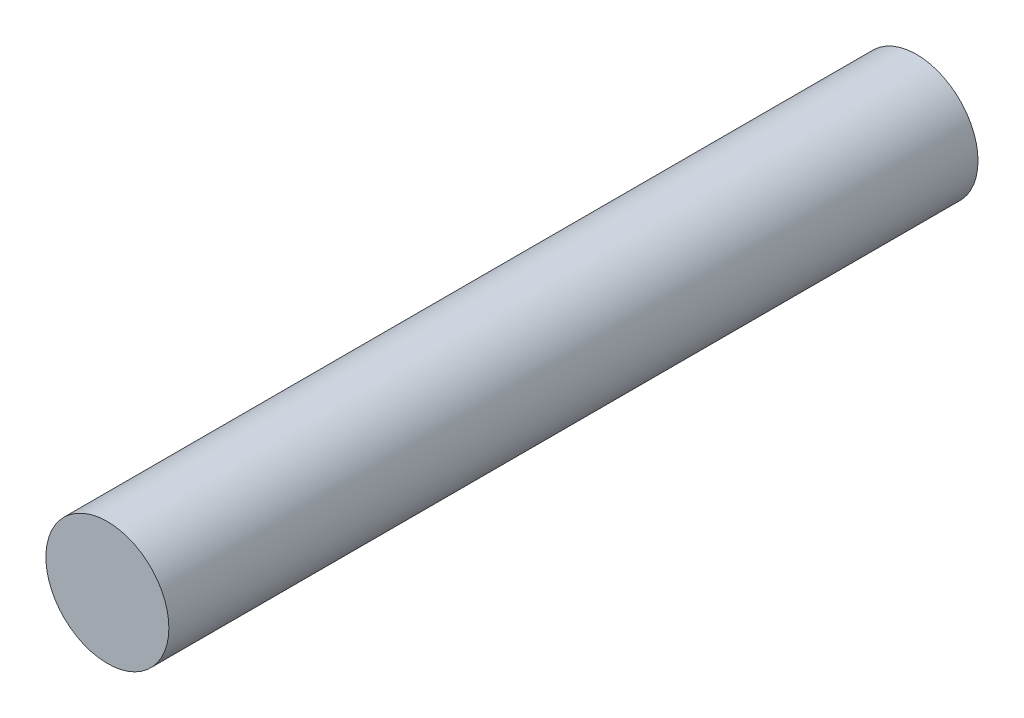
SolidWorks part; units mm, degrees
ref_plane "Front Plane" through (0, 0, 0) normal (0, 0, 1) x (1, 0, 0)
ref_plane "Top Plane" through (0, 0, 0) normal (0, 1, 0) x (1, 0, 0)
ref_plane "Right Plane" through (0, 0, 0) normal (1, 0, 0) x (0, 0, -1)
sketch "Sketch1" plane through (0, 0, 0) normal (0, 0, 1) x (1, 0, 0)
  circle A0 centre (0, 0) radius 19
  dimension "D1" = 38
extrude "Boss-Extrude1" add sketch "Sketch1" along normal blind 250
